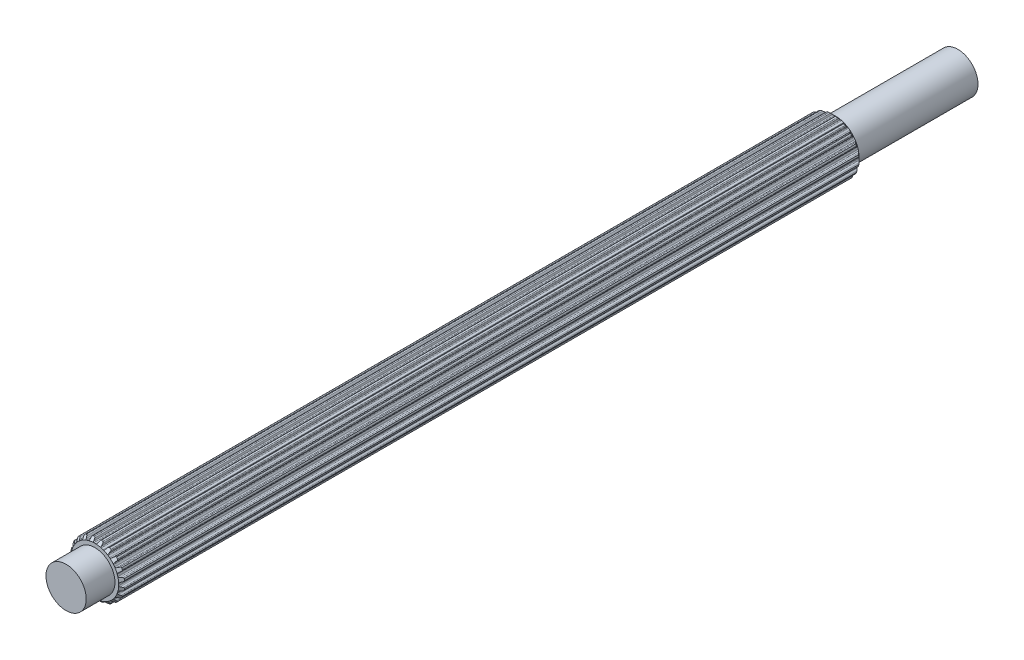
SolidWorks part; units mm, degrees
ref_plane "Front Plane" through (0, 0, 0) normal (0, 0, 1) x (1, 0, 0)
ref_plane "Top Plane" through (0, 0, 0) normal (0, 1, 0) x (1, 0, 0)
ref_plane "Right Plane" through (0, 0, 0) normal (1, 0, 0) x (0, 0, -1)
sketch "Sketch1" plane through (0, 0, 0) normal (0, 0, 1) x (1, 0, 0)
  line L0 (-0.1069, 2.9699) -> (0.1069, 2.9699)
  line L1 (0.3159, 3.2375) -> (0.2537, 3.0575)
  line L2 (-0.2964, 3.2367) -> (-0.2318, 3.0575)
  line L3 (-0.2964, 3.2367) -> (0.3159, 3.2375) construction
  line L4 (0, 3.3252) -> (0, 0) construction
  line L5 (-0.2318, 3.0575) -> (0.2537, 3.0575) construction
  line L6 (-0.4281, 3.3241) -> (0.4281, 3.3263) construction
  line L7 (0.7183, 3.1698) -> (0.7244, 2.9795)
  line L8 (0.816, 2.8576) -> (1.0195, 2.7915)
  line L9 (1.3009, 2.9815) -> (1.1862, 2.8295)
  line L10 (1.6627, 2.7927) -> (1.6097, 2.6099)
  line L11 (1.6591, 2.4655) -> (1.8322, 2.3398)
  line L12 (2.1585, 2.4335) -> (2.0025, 2.3245)
  line L13 (2.4443, 2.1423) -> (2.3374, 1.9847)
  line L14 (2.3398, 1.8322) -> (2.4655, 1.6591)
  line L15 (2.8049, 1.6474) -> (2.6228, 1.5919)
  line L16 (2.9866, 1.2821) -> (2.8363, 1.1653)
  line L17 (2.7915, 1.0195) -> (2.8576, 0.816)
  line L18 (3.1767, 0.7) -> (2.9863, 0.7035)
  line L19 (3.2367, 0.2964) -> (3.0575, 0.2318)
  line L20 (2.9699, 0.1069) -> (2.9699, -0.1069)
  line L21 (3.2375, -0.3159) -> (3.0575, -0.2537)
  line L22 (3.1698, -0.7183) -> (2.9795, -0.7244)
  line L23 (2.8576, -0.816) -> (2.7915, -1.0195)
  line L24 (2.9815, -1.3009) -> (2.8295, -1.1862)
  line L25 (2.7927, -1.6627) -> (2.6099, -1.6097)
  line L26 (2.4655, -1.6591) -> (2.3398, -1.8322)
  line L27 (2.4335, -2.1585) -> (2.3245, -2.0025)
  line L28 (2.1423, -2.4443) -> (1.9847, -2.3374)
  line L29 (1.8322, -2.3398) -> (1.6591, -2.4655)
  line L30 (1.6474, -2.8049) -> (1.5919, -2.6228)
  line L31 (1.2821, -2.9866) -> (1.1653, -2.8363)
  line L32 (1.0195, -2.7915) -> (0.816, -2.8576)
  line L33 (0.7, -3.1767) -> (0.7035, -2.9863)
  line L34 (0.2964, -3.2367) -> (0.2318, -3.0575)
  line L35 (0.1069, -2.9699) -> (-0.1069, -2.9699)
  line L36 (-0.3159, -3.2375) -> (-0.2537, -3.0575)
  line L37 (-0.7183, -3.1698) -> (-0.7244, -2.9795)
  line L38 (-0.816, -2.8576) -> (-1.0195, -2.7915)
  line L39 (-1.3009, -2.9815) -> (-1.1862, -2.8295)
  line L40 (-1.6627, -2.7927) -> (-1.6097, -2.6099)
  line L41 (-1.6591, -2.4655) -> (-1.8322, -2.3398)
  line L42 (-2.1585, -2.4335) -> (-2.0025, -2.3245)
  line L43 (-2.4443, -2.1423) -> (-2.3374, -1.9847)
  line L44 (-2.3398, -1.8322) -> (-2.4655, -1.6591)
  line L45 (-2.8049, -1.6474) -> (-2.6228, -1.5919)
  line L46 (-2.9866, -1.2821) -> (-2.8363, -1.1653)
  line L47 (-2.7915, -1.0195) -> (-2.8576, -0.816)
  line L48 (-3.1767, -0.7) -> (-2.9863, -0.7035)
  line L49 (-3.2367, -0.2964) -> (-3.0575, -0.2318)
  line L50 (-2.9699, -0.1069) -> (-2.9699, 0.1069)
  line L51 (-3.2375, 0.3159) -> (-3.0575, 0.2537)
  line L52 (-3.1698, 0.7183) -> (-2.9795, 0.7244)
  line L53 (-2.8576, 0.816) -> (-2.7915, 1.0195)
  line L54 (-2.9815, 1.3009) -> (-2.8295, 1.1862)
  line L55 (-2.7927, 1.6627) -> (-2.6099, 1.6097)
  line L56 (-2.4655, 1.6591) -> (-2.3398, 1.8322)
  line L57 (-2.4335, 2.1585) -> (-2.3245, 2.0025)
  line L58 (-2.1423, 2.4443) -> (-1.9847, 2.3374)
  line L59 (-1.8322, 2.3398) -> (-1.6591, 2.4655)
  line L60 (-1.6474, 2.8049) -> (-1.5919, 2.6228)
  line L61 (-1.2821, 2.9866) -> (-1.1653, 2.8363)
  line L62 (-1.0195, 2.7915) -> (-0.816, 2.8576)
  line L63 (-0.7, 3.1767) -> (-0.7035, 2.9863)
  line L64 (0.4281, 3.3263) -> (0.62, 3.2938)
  line L65 (1.4351, 3.0312) -> (1.6075, 2.9409)
  line L66 (2.3015, 2.4394) -> (2.4376, 2.3003)
  line L67 (2.9427, 1.6088) -> (3.0291, 1.4344)
  line L68 (3.2958, 0.6207) -> (3.3241, 0.4281)
  line L69 (3.3263, -0.4281) -> (3.2938, -0.62)
  line L70 (3.0312, -1.4351) -> (2.9409, -1.6075)
  line L71 (2.4394, -2.3015) -> (2.3003, -2.4376)
  line L72 (1.6088, -2.9427) -> (1.4344, -3.0291)
  line L73 (0.6207, -3.2958) -> (0.4281, -3.3241)
  line L74 (-0.4281, -3.3263) -> (-0.62, -3.2938)
  line L75 (-1.4351, -3.0312) -> (-1.6075, -2.9409)
  line L76 (-2.3015, -2.4394) -> (-2.4376, -2.3003)
  line L77 (-2.9427, -1.6088) -> (-3.0291, -1.4344)
  line L78 (-3.2958, -0.6207) -> (-3.3241, -0.4281)
  line L79 (-3.3263, 0.4281) -> (-3.2938, 0.62)
  line L80 (-3.0312, 1.4351) -> (-2.9409, 1.6075)
  line L81 (-2.4394, 2.3015) -> (-2.3003, 2.4376)
  line L82 (-1.6088, 2.9427) -> (-1.4344, 3.0291)
  line L83 (-0.6207, 3.2958) -> (-0.4281, 3.3241)
  arc A0 (0.2537, 3.0575) -> (0.1069, 2.9699) centre (0.1283, 3.1009) cw
  arc A1 (-0.2318, 3.0575) -> (-0.1069, 2.9699) centre (-0.1069, 3.1026) ccw
  arc A2 (0.62, 3.2938) -> (0.7183, 3.1698) centre (0.5856, 3.1656) cw
  arc A3 (0.7244, 2.9795) -> (0.816, 2.8576) centre (0.857, 2.9838) ccw
  arc A4 (-0.4281, 3.3241) -> (-0.2964, 3.2367) centre (-0.4213, 3.1916) cw
  arc A5 (0.4281, 3.3263) -> (0.3159, 3.2375) centre (0.4413, 3.1942) ccw
  arc A6 (1.1862, 2.8295) -> (1.0195, 2.7915) centre (1.0802, 2.9095) cw
  arc A7 (1.4351, 3.0312) -> (1.3009, 2.9815) centre (1.4068, 2.9015) ccw
  arc A8 (1.6075, 2.9409) -> (1.6627, 2.7927) centre (1.5352, 2.8297) cw
  arc A9 (1.6097, 2.6099) -> (1.6591, 2.4655) centre (1.7371, 2.5729) ccw
  arc A10 (2.0025, 2.3245) -> (1.8322, 2.3398) centre (1.9264, 2.4332) cw
  arc A11 (2.3015, 2.4394) -> (2.1585, 2.4335) centre (2.2346, 2.3248) ccw
  arc A12 (2.4376, 2.3003) -> (2.4443, 2.1423) centre (2.3345, 2.2168) cw
  arc A13 (2.3374, 1.9847) -> (2.3398, 1.8322) centre (2.4472, 1.9102) ccw
  arc A14 (2.6228, 1.5919) -> (2.4655, 1.6591) centre (2.5841, 1.7189) cw
  arc A15 (2.9427, 1.6088) -> (2.8049, 1.6474) centre (2.8436, 1.5205) ccw
  arc A16 (3.0291, 1.4344) -> (2.9866, 1.2821) centre (2.9052, 1.3869) cw
  arc A17 (2.8363, 1.1653) -> (2.7915, 1.0195) centre (2.9177, 1.0605) ccw
  arc A18 (2.9863, 0.7035) -> (2.8576, 0.816) centre (2.9887, 0.8362) cw
  arc A19 (3.2958, 0.6207) -> (3.1767, 0.7) centre (3.1743, 0.5673) ccw
  arc A20 (3.3241, 0.4281) -> (3.2367, 0.2964) centre (3.1916, 0.4213) cw
  arc A21 (3.0575, 0.2318) -> (2.9699, 0.1069) centre (3.1026, 0.1069) ccw
  arc A22 (3.0575, -0.2537) -> (2.9699, -0.1069) centre (3.1009, -0.1283) cw
  arc A23 (3.3263, -0.4281) -> (3.2375, -0.3159) centre (3.1942, -0.4413) ccw
  arc A24 (3.2938, -0.62) -> (3.1698, -0.7183) centre (3.1656, -0.5856) cw
  arc A25 (2.9795, -0.7244) -> (2.8576, -0.816) centre (2.9838, -0.857) ccw
  arc A26 (2.8295, -1.1862) -> (2.7915, -1.0195) centre (2.9095, -1.0802) cw
  arc A27 (3.0312, -1.4351) -> (2.9815, -1.3009) centre (2.9015, -1.4068) ccw
  arc A28 (2.9409, -1.6075) -> (2.7927, -1.6627) centre (2.8297, -1.5352) cw
  arc A29 (2.6099, -1.6097) -> (2.4655, -1.6591) centre (2.5729, -1.7371) ccw
  arc A30 (2.3245, -2.0025) -> (2.3398, -1.8322) centre (2.4332, -1.9264) cw
  arc A31 (2.4394, -2.3015) -> (2.4335, -2.1585) centre (2.3248, -2.2346) ccw
  arc A32 (2.3003, -2.4376) -> (2.1423, -2.4443) centre (2.2168, -2.3345) cw
  arc A33 (1.9847, -2.3374) -> (1.8322, -2.3398) centre (1.9102, -2.4472) ccw
  arc A34 (1.5919, -2.6228) -> (1.6591, -2.4655) centre (1.7189, -2.5841) cw
  arc A35 (1.6088, -2.9427) -> (1.6474, -2.8049) centre (1.5205, -2.8436) ccw
  arc A36 (1.4344, -3.0291) -> (1.2821, -2.9866) centre (1.3869, -2.9052) cw
  arc A37 (1.1653, -2.8363) -> (1.0195, -2.7915) centre (1.0605, -2.9177) ccw
  arc A38 (0.7035, -2.9863) -> (0.816, -2.8576) centre (0.8362, -2.9887) cw
  arc A39 (0.6207, -3.2958) -> (0.7, -3.1767) centre (0.5673, -3.1743) ccw
  arc A40 (0.4281, -3.3241) -> (0.2964, -3.2367) centre (0.4213, -3.1916) cw
  arc A41 (0.2318, -3.0575) -> (0.1069, -2.9699) centre (0.1069, -3.1026) ccw
  arc A42 (-0.2537, -3.0575) -> (-0.1069, -2.9699) centre (-0.1283, -3.1009) cw
  arc A43 (-0.4281, -3.3263) -> (-0.3159, -3.2375) centre (-0.4413, -3.1942) ccw
  arc A44 (-0.62, -3.2938) -> (-0.7183, -3.1698) centre (-0.5856, -3.1656) cw
  arc A45 (-0.7244, -2.9795) -> (-0.816, -2.8576) centre (-0.857, -2.9838) ccw
  arc A46 (-1.1862, -2.8295) -> (-1.0195, -2.7915) centre (-1.0802, -2.9095) cw
  arc A47 (-1.4351, -3.0312) -> (-1.3009, -2.9815) centre (-1.4068, -2.9015) ccw
  arc A48 (-1.6075, -2.9409) -> (-1.6627, -2.7927) centre (-1.5352, -2.8297) cw
  arc A49 (-1.6097, -2.6099) -> (-1.6591, -2.4655) centre (-1.7371, -2.5729) ccw
  arc A50 (-2.0025, -2.3245) -> (-1.8322, -2.3398) centre (-1.9264, -2.4332) cw
  arc A51 (-2.3015, -2.4394) -> (-2.1585, -2.4335) centre (-2.2346, -2.3248) ccw
  arc A52 (-2.4376, -2.3003) -> (-2.4443, -2.1423) centre (-2.3345, -2.2168) cw
  arc A53 (-2.3374, -1.9847) -> (-2.3398, -1.8322) centre (-2.4472, -1.9102) ccw
  arc A54 (-2.6228, -1.5919) -> (-2.4655, -1.6591) centre (-2.5841, -1.7189) cw
  arc A55 (-2.9427, -1.6088) -> (-2.8049, -1.6474) centre (-2.8436, -1.5205) ccw
  arc A56 (-3.0291, -1.4344) -> (-2.9866, -1.2821) centre (-2.9052, -1.3869) cw
  arc A57 (-2.8363, -1.1653) -> (-2.7915, -1.0195) centre (-2.9177, -1.0605) ccw
  arc A58 (-2.9863, -0.7035) -> (-2.8576, -0.816) centre (-2.9887, -0.8362) cw
  arc A59 (-3.2958, -0.6207) -> (-3.1767, -0.7) centre (-3.1743, -0.5673) ccw
  arc A60 (-3.3241, -0.4281) -> (-3.2367, -0.2964) centre (-3.1916, -0.4213) cw
  arc A61 (-3.0575, -0.2318) -> (-2.9699, -0.1069) centre (-3.1026, -0.1069) ccw
  arc A62 (-3.0575, 0.2537) -> (-2.9699, 0.1069) centre (-3.1009, 0.1283) cw
  arc A63 (-3.3263, 0.4281) -> (-3.2375, 0.3159) centre (-3.1942, 0.4413) ccw
  arc A64 (-3.2938, 0.62) -> (-3.1698, 0.7183) centre (-3.1656, 0.5856) cw
  arc A65 (-2.9795, 0.7244) -> (-2.8576, 0.816) centre (-2.9838, 0.857) ccw
  arc A66 (-2.8295, 1.1862) -> (-2.7915, 1.0195) centre (-2.9095, 1.0802) cw
  arc A67 (-3.0312, 1.4351) -> (-2.9815, 1.3009) centre (-2.9015, 1.4068) ccw
  arc A68 (-2.9409, 1.6075) -> (-2.7927, 1.6627) centre (-2.8297, 1.5352) cw
  arc A69 (-2.6099, 1.6097) -> (-2.4655, 1.6591) centre (-2.5729, 1.7371) ccw
  arc A70 (-2.3245, 2.0025) -> (-2.3398, 1.8322) centre (-2.4332, 1.9264) cw
  arc A71 (-2.4394, 2.3015) -> (-2.4335, 2.1585) centre (-2.3248, 2.2346) ccw
  arc A72 (-2.3003, 2.4376) -> (-2.1423, 2.4443) centre (-2.2168, 2.3345) cw
  arc A73 (-1.9847, 2.3374) -> (-1.8322, 2.3398) centre (-1.9102, 2.4472) ccw
  arc A74 (-1.5919, 2.6228) -> (-1.6591, 2.4655) centre (-1.7189, 2.5841) cw
  arc A75 (-1.6088, 2.9427) -> (-1.6474, 2.8049) centre (-1.5205, 2.8436) ccw
  arc A76 (-1.4344, 3.0291) -> (-1.2821, 2.9866) centre (-1.3869, 2.9052) cw
  arc A77 (-1.1653, 2.8363) -> (-1.0195, 2.7915) centre (-1.0605, 2.9177) ccw
  arc A78 (-0.7035, 2.9863) -> (-0.816, 2.8576) centre (-0.8362, 2.9887) cw
  arc A79 (-0.6207, 3.2958) -> (-0.7, 3.1767) centre (-0.5673, 3.1743) ccw
  point P14 (0, 2.9699)
  point P247 (0, 0)
  dimension "D4" = 0.1327
  dimension "D8" = 20
  dimension "D1" = 2.9699
  dimension "D2" = 0.2139
  dimension "D3" = 0.1904
  dimension "D5" = 0.0877
  dimension "D6" = 0.4855
  dimension "D7" = 0.8563
extrude "Boss-Extrude1" add sketch "Sketch1" along normal mid plane 92.0953
sketch "Sketch2" plane through (0, 0, 0) normal (0, 0, 1) x (1, 0, 0)
  circle A0 centre (0, 0) radius 2.5019
  dimension "D1" = 5.0038
extrude "Boss-Extrude2" add sketch "Sketch2" along normal blind 49.6291 and the other way blind 61.3131
sketch "Sketch4" plane through (0, 0, 49.6291) normal (0, 0, 1) x (1, 0, 0)
  circle A0 centre (0, 0) radius 2.5019 construction
  point P0 (0, 0)
sketch "Sketch5" plane through (0, 0, -61.3131) normal (0, 0, -1) x (-1, 0, 0)
  circle A0 centre (0, 0) radius 2.5019 construction
  point P0 (0, 0)
sketch "Sketch3" plane through (0, 0, 0) normal (1, 0, 0) x (0, 0, -1)
  line L0 (-44.9164, 4.1011) -> (-46.0477, 2.9699)
  line L1 (-46.0477, 2.9699) -> (-46.0477, 4.1011)
  line L2 (-46.0477, 4.1011) -> (-44.9164, 4.1011)
  line L3 (-46.0477, 2.5019) -> (-46.0477, -2.5019) construction
  line L5 (-14.3608, 0) -> (13.2171, 0) construction
  line L7 (46.0477, 42.7615) -> (46.0477, 2.9699)
  line L8 (46.0477, 2.9699) -> (26.1518, 22.8657)
  line L9 (26.1518, 22.8657) -> (46.0477, 42.7615)
  line L10 (46.0477, -2.5019) -> (46.0477, 2.5019) construction
  point P6 (-4.866, 6.1438)
  dimension "D1" = 45
  dimension "D2" = 45
revolve "Cut-Revolve1" cut sketch "Sketch3" angle 360 about L5
sketch "Sketch6" plane through (0, 0, 0) normal (0, 1, 0) x (1, 0, 0)
  line L0 (-15.5223, 0) -> (15.5223, 0) construction
